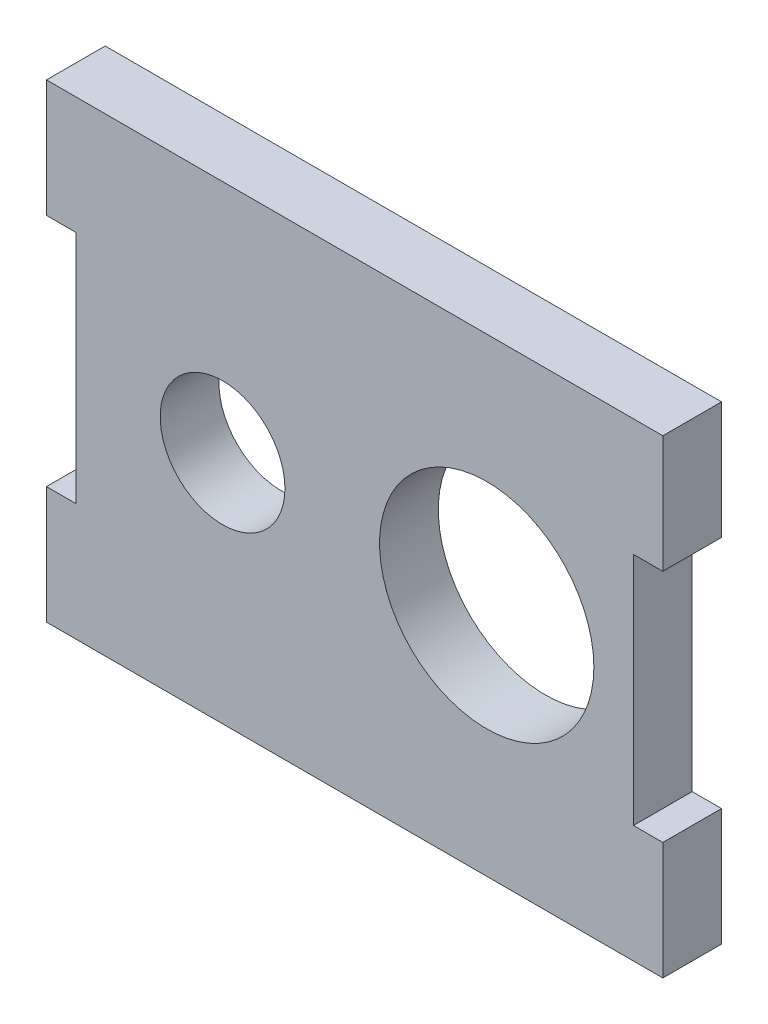
SolidWorks part; units mm, degrees
ref_plane "Front" through (0, 0, 0) normal (0, 0, 1) x (1, 0, 0)
ref_plane "Top" through (0, 0, 0) normal (0, 1, 0) x (1, 0, 0)
ref_plane "Right" through (0, 0, 0) normal (1, 0, 0) x (0, 0, -1)
sketch "Sketch1" plane through (0, 0, 0) normal (0, 0, 1) x (1, 0, 0)
  line L0 (528.697, -398.6735) -> (537.697, -398.6735) construction
  line L1 (543.697, -406.6735) -> (522.697, -406.6735)
  line L2 (543.697, -406.6735) -> (543.697, -402.6735)
  line L3 (543.697, -390.6735) -> (522.697, -390.6735)
  line L4 (522.697, -406.6735) -> (522.697, -402.6735)
  line L5 (542.697, -402.6735) -> (543.697, -402.6735)
  line L6 (522.697, -394.6735) -> (523.697, -394.6735)
  line L8 (522.697, -402.6735) -> (523.697, -402.6735)
  line L9 (523.697, -394.6735) -> (523.697, -402.6735)
  line L10 (542.697, -394.6735) -> (542.697, -402.6735)
  line L11 (542.697, -394.6735) -> (543.697, -394.6735)
  line L13 (543.697, -394.6735) -> (543.697, -390.6735)
  line L14 (522.697, -394.6735) -> (522.697, -390.6735)
  circle A0 centre (537.697, -398.6735) radius 3.65
  circle A1 centre (528.697, -398.6735) radius 2.125
  dimension "D4" = 8
  dimension "D1" = 21
  dimension "D2" = 16
  dimension "D3" = 9
extrude "Extrude1" add sketch "Sketch1" along normal blind 2
